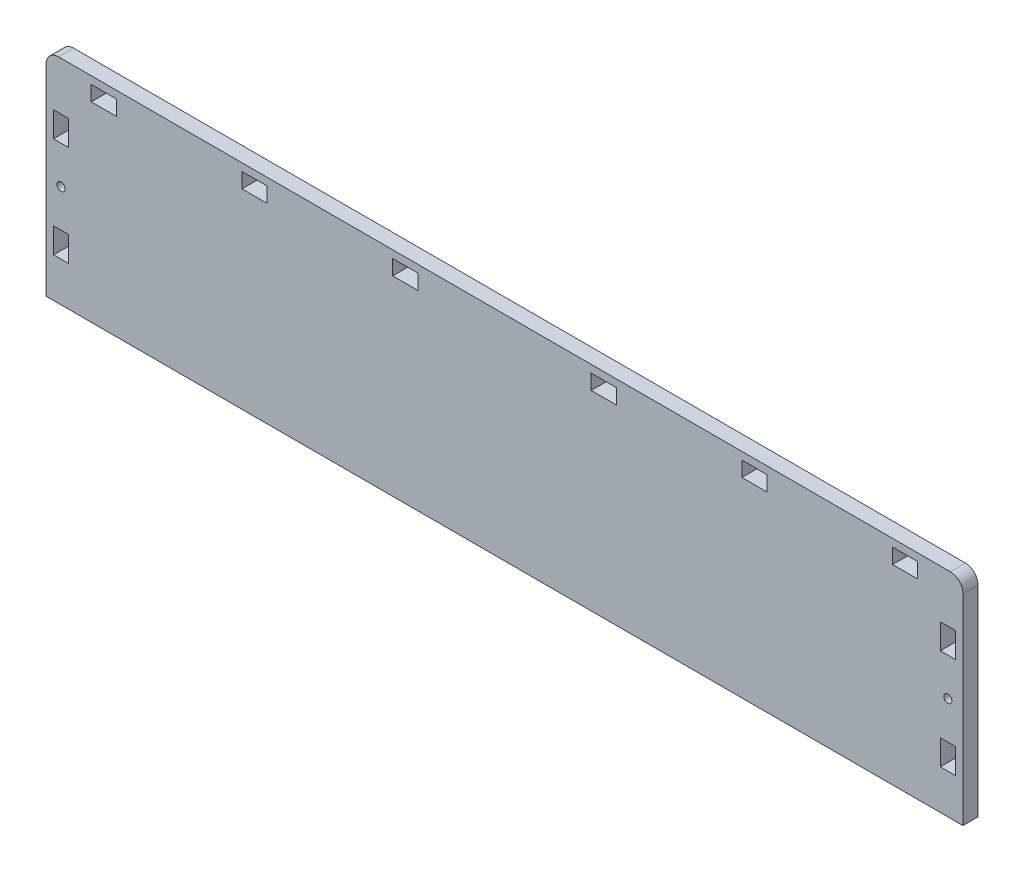
SolidWorks part; units mm, degrees
material "Клен"
ref_plane "Спереди" through (0, 0, 0) normal (0, 0, 1) x (1, 0, 0)
ref_plane "Сверху" through (0, 0, 0) normal (0, 1, 0) x (1, 0, 0)
ref_plane "Справа" through (0, 0, 0) normal (1, 0, 0) x (0, 0, -1)
sketch "Эскиз1" plane through (0, 0, 0) normal (0, 0, 1) x (1, 0, 0)
  line L0 (3, 79.6141) -> (3, -130.8498) construction
  line L1 (5, 0) -> (360, 0)
  line L2 (0, -5) -> (0, -85)
  line L3 (0, -85) -> (365, -85)
  line L4 (365, -5) -> (365, -85)
  line L5 (9, 79.6141) -> (9, -130.8498) construction
  line L6 (362, 64.2326) -> (362, -113.6119) construction
  line L7 (356, 64.2326) -> (356, -113.5925) construction
  line L8 (377.6958, -44.2517) -> (-29.2423, -44.2517) construction
  line L9 (6, -42.4454) -> (6, -48.0377) construction
  line L10 (182.5, 14.7778) -> (182.5, -113.5925) construction
  line L11 (9, -69.2517) -> (9, -59.2517)
  line L12 (3, -19.2517) -> (9, -19.2517)
  line L13 (3, -19.2517) -> (3, -29.2517)
  line L14 (3, -29.2517) -> (9, -29.2517)
  line L15 (9, -19.2517) -> (9, -29.2517)
  line L16 (3, -59.2517) -> (9, -59.2517)
  line L17 (3, -69.2517) -> (3, -59.2517)
  line L18 (3, -69.2517) -> (9, -69.2517)
  line L19 (359, -42.4454) -> (359, -48.0377) construction
  line L20 (356, -19.2517) -> (356, -29.2517)
  line L21 (362, -29.2517) -> (356, -29.2517)
  line L22 (362, -19.2517) -> (362, -29.2517)
  line L23 (362, -19.2517) -> (356, -19.2517)
  line L24 (362, -69.2517) -> (356, -69.2517)
  line L25 (362, -69.2517) -> (362, -59.2517)
  line L26 (362, -59.2517) -> (356, -59.2517)
  line L27 (356, -69.2517) -> (356, -59.2517)
  line L28 (19.2237, -3) -> (44.4484, -3) construction
  line L29 (78, -3) -> (78, -9)
  line L30 (18, -3) -> (28, -3)
  line L31 (18, -3) -> (18, -9)
  line L32 (18, -9) -> (28, -9)
  line L33 (28, -3) -> (28, -9)
  line L34 (78, -3) -> (88, -3)
  line L35 (88, -3) -> (88, -9)
  line L36 (78, -9) -> (88, -9)
  line L37 (138, -3) -> (138, -9)
  line L38 (138, -3) -> (148, -3)
  line L39 (148, -3) -> (148, -9)
  line L40 (138, -9) -> (148, -9)
  line L41 (227, -3) -> (217, -3)
  line L42 (217, -3) -> (217, -9)
  line L43 (227, -9) -> (217, -9)
  line L44 (227, -3) -> (227, -9)
  line L45 (287, -3) -> (277, -3)
  line L46 (277, -3) -> (277, -9)
  line L47 (287, -9) -> (277, -9)
  line L48 (287, -3) -> (287, -9)
  line L49 (347, -9) -> (337, -9)
  line L50 (337, -3) -> (337, -9)
  line L51 (347, -3) -> (337, -3)
  line L52 (347, -3) -> (347, -9)
  arc A0 (360, 0) -> (365, -5) centre (360, -5) cw
  arc A1 (5, 0) -> (0, -5) centre (5, -5) ccw
  circle A2 centre (6, -44.2517) radius 1.6
  circle A3 centre (359, -44.2517) radius 1.6
  point P7 (365, 0)
  point P10 (0, 0)
  dimension "D3" = 5
  dimension "D9" = 3.2
  dimension "D1" = 365
  dimension "D2" = 85
  dimension "D4" = 3
  dimension "D5" = 6
  dimension "D6" = 3
  dimension "D7" = 6
  dimension "D8" = 3
  dimension "D10" = 10
  dimension "D11" = 15
  dimension "D12" = 3
  dimension "D13" = 6
  dimension "D14" = 10
  dimension "D15" = 18
  dimension "D16" = 3
extrude "Бобышка-Вытянуть1" add sketch "Эскиз1" along normal blind 6
